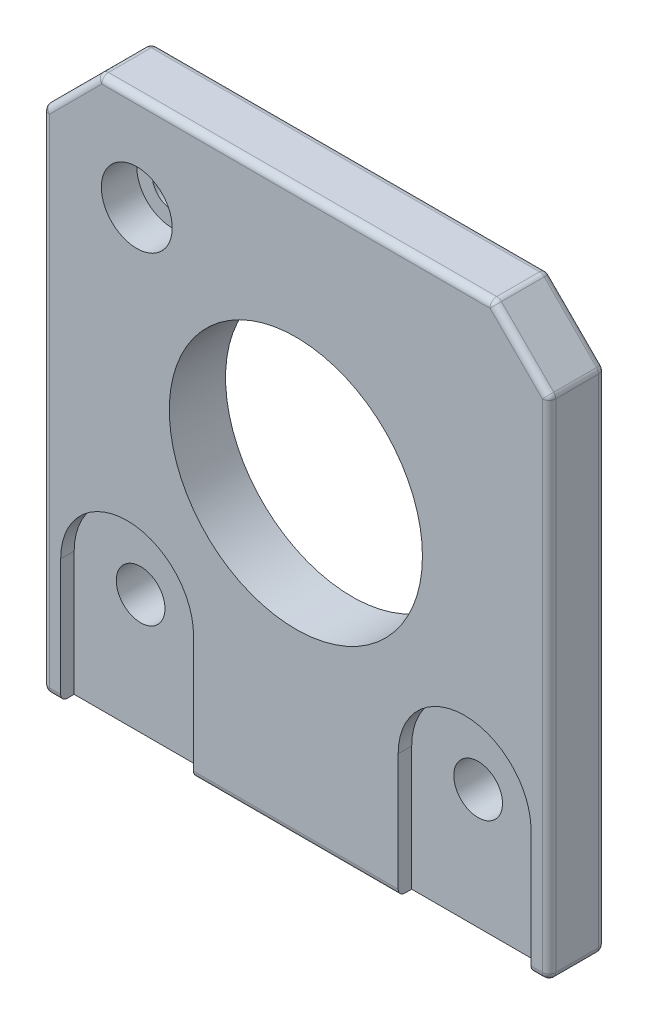
SolidWorks part; units mm, degrees
material "PLA"
ref_plane "Front Plane" through (0, 0, 0) normal (0, 0, 1) x (1, 0, 0)
ref_plane "Top Plane" through (0, 0, 0) normal (0, 1, 0) x (1, 0, 0)
ref_plane "Right Plane" through (0, 0, 0) normal (1, 0, 0) x (0, 0, -1)
sketch "Sketch2" plane through (0, 0, 0) normal (0, 1, 0) x (1, 0, 0)
  line L1 (-28.575, 3.175) -> (28.575, 3.175)
  line L2 (-28.575, 3.175) -> (-28.575, -3.175)
  line L3 (-28.575, -3.175) -> (28.575, -3.175)
  line L4 (28.575, 3.175) -> (28.575, -3.175)
  point P4 (0, 3.175)
  point P7 (-28.575, 0)
  dimension "D1" = 6.35
  dimension "D2" = 57.15
extrude "Boss-Extrude1" add sketch "Sketch2" against normal blind 63.5
sketch "Sketch3" plane through (0, 0, 3.175) normal (0, 0, 1) x (1, 0, 0)
  line L2 (-28.575, 0) -> (28.575, 0) construction
  circle A0 centre (0, -28.815) radius 14.2875
  point P2 (0, 0)
  dimension "D1" = 28.815
  dimension "D3" = 28.575
extrude "Cut-Extrude1" cut sketch "Sketch3" against normal through all
chamfer "Chamfer1" distance 6.35 angle 45 2 edges at (-28.575, 0, 0) (28.575, 0, 0)
hole_wizard "M5 Clearance Hole1" positions "Sketch6" profile "Sketch7" hole size "M5" standard "ANSI Metric" end condition through all
sketch "Sketch6" plane through (0, 0, 3.175) normal (0, 0, 1) x (1, 0, 0)
  line L0 (-28.575, -63.5) -> (28.575, -63.5) construction
  line L1 (28.575, -63.5) -> (28.575, -6.35) construction
  point P0 (-19.05, -50)
  point P3 (19.05, -50)
  dimension "D1" = 13.5
  dimension "D2" = 9.525
  dimension "D3" = 38.1
sketch "Sketch7" plane through (-19.05, -50, 3.175) normal (1, 0, 0) x (0, -1, 0)
  line L0 (0, 0) -> (0, 6.35)
  line L1 (0, 6.35) -> (2.75, 6.35)
  line L2 (2.75, 6.35) -> (2.75, 0)
  line L5 (2.75, 0) -> (0, 0)
  line L11 (0, -6.35) -> (0, 107.95) construction
  dimension "Thru Hole Dia." = 5.5
  dimension "Thru Hole Depth" = 6.35
fillet "Fillet1" radius 0.762 18 edges at (0, -63.5, 3.175) (0, -63.5, -3.175) (28.575, -63.5, 0) (28.575, -34.925, 3.175) (28.575, -34.925, -3.175) (-28.575, -63.5, 0) (-28.575, -34.925, -3.175) (-28.575, -34.925, 3.175) (-25.4, -3.175, 3.175) (-28.575, -6.35, 0) (-25.4, -3.175, -3.175) (0, 0, 3.175) (-22.225, 0, 0) (0, 0, -3.175) (22.225, 0, 0) (25.4, -3.175, -3.175) (28.575, -6.35, 0) (25.4, -3.175, 3.175)
sketch "Sketch8" plane through (0, 0, 3.175) normal (0, 0, 1) x (1, 0, 0)
  line L0 (11.55, -63.5) -> (11.55, -49.5)
  line L1 (26.55, -49.5) -> (26.55, -63.5)
  line L2 (11.55, -63.5) -> (26.55, -63.5)
  line L3 (28.575, -63.5) -> (28.575, -6.35) construction
  line L4 (-28.575, -63.5) -> (28.575, -63.5) construction
  arc A0 (11.55, -49.5) -> (26.55, -49.5) centre (19.05, -49.5) cw
  dimension "D2" = 7.5
  dimension "D1" = 2.025
  dimension "D3" = 14
  dimension "D4" = 15
extrude "Cut-Extrude4" cut sketch "Sketch8" against normal blind 1.524
mirror "Mirror1" about plane through (0, 0, 0) normal (1, 0, 0) of "Cut-Extrude4"
hole_wizard "CBORE for M4 SHCS2" positions "Sketch9" profile "Sketch10" counterbore size "M4" standard "ANSI Metric" end condition through all
sketch "Sketch9" plane through (0, 0, 3.175) normal (0, 0, 1) x (1, 0, 0)
  line L0 (-21.9094, 0) -> (21.9094, 0) construction
  point P0 (-17.9605, -10.8545)
  dimension "D1" = 10.8545
  dimension "D2" = 17.9605
sketch "Sketch10" plane through (-17.9605, -10.8545, 3.175) normal (1, 0, 0) x (0, -1, 0)
  line L0 (0, 0) -> (0, 6.35)
  line L1 (0, 6.35) -> (2.25, 6.35)
  line L3 (2.25, 6.35) -> (2.25, 4)
  line L4 (2.25, 4) -> (4, 4)
  line L5 (4, 4) -> (4, 0)
  line L7 (4, 0) -> (0, 0)
  line L11 (0, -6.35) -> (0, 107.95) construction
  dimension "Thru Hole Dia." = 4.5
  dimension "Thru Hole Depth" = 6.35
  dimension "C'Bore Dia." = 8
  dimension "C'Bore Depth" = 4
